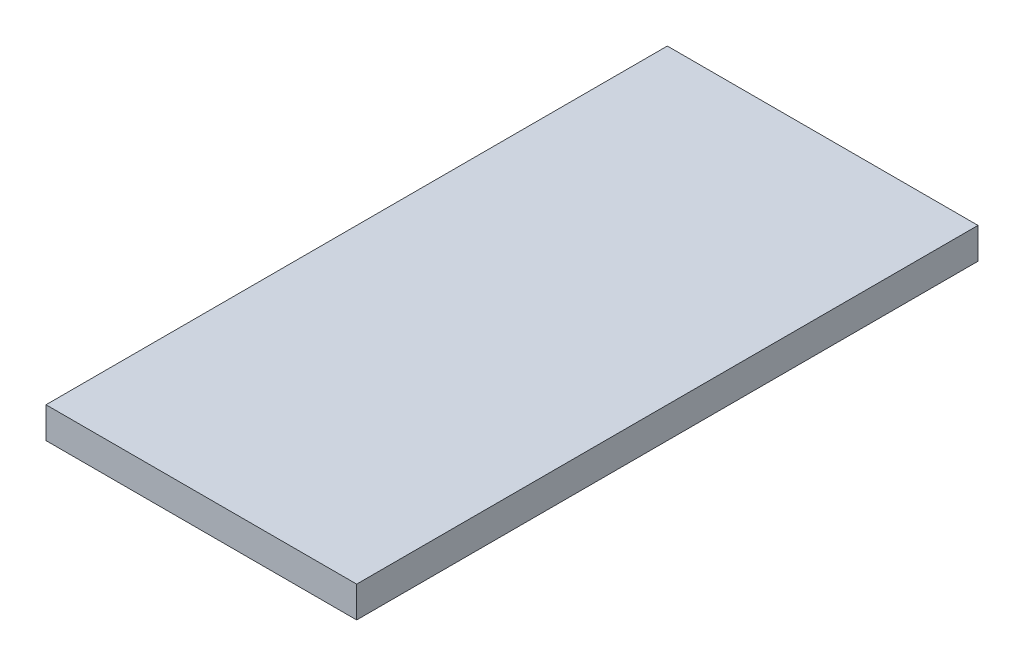
SolidWorks part; units mm, degrees
ref_plane "Front Plane" through (0, 0, 0) normal (0, 0, 1) x (1, 0, 0)
ref_plane "Top Plane" through (0, 0, 0) normal (0, 1, 0) x (1, 0, 0)
ref_plane "Right Plane" through (0, 0, 0) normal (1, 0, 0) x (0, 0, -1)
sketch "Sketch1" plane through (0, 0, 0) normal (0, 1, 0) x (1, 0, 0)
  line L0 (0, 0) -> (0, -20)
  line L1 (0, 0) -> (10, 0)
  line L2 (10, 0) -> (10, -20)
  line L3 (0, -20) -> (10, -20)
  dimension "D1" = 20
  dimension "D2" = 10
extrude "Boss-Extrude1" add sketch "Sketch1" along normal blind 1
ref_plane "Plane1" through (0, 0.5, 0) normal (0, 1, 0) x (1, 0, 0)
